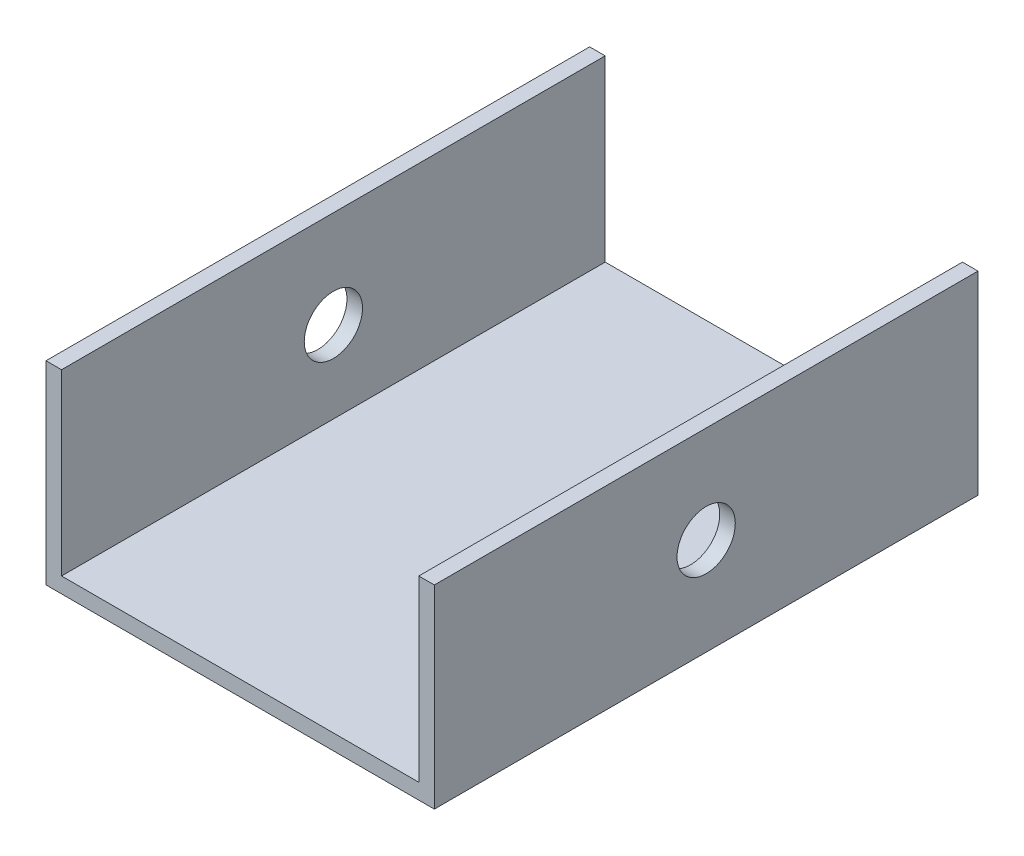
SolidWorks part; units mm, degrees
ref_plane "Front Plane" through (0, 0, 0) normal (0, 0, 1) x (1, 0, 0)
ref_plane "Top Plane" through (0, 0, 0) normal (0, 1, 0) x (1, 0, 0)
ref_plane "Right Plane" through (0, 0, 0) normal (1, 0, 0) x (0, 0, -1)
sketch "Sketch1" plane through (0, 0, 0) normal (0, 0, 1) x (1, 0, 0)
  line L0 (-38.8242, 25.8663) -> (-34.8242, 25.8663)
  line L1 (57.1758, 25.8663) -> (61.1758, 25.8663)
  line L2 (-38.8242, 25.8663) -> (-38.8242, -24.1337)
  line L3 (-38.8242, -24.1337) -> (61.1758, -24.1337)
  line L4 (61.1758, 25.8663) -> (61.1758, -24.1337)
  line L5 (-34.8242, 25.8663) -> (-34.8242, -20.1337)
  line L6 (-34.8242, -20.1337) -> (57.1758, -20.1337)
  line L7 (57.1758, 25.8663) -> (57.1758, -20.1337)
  dimension "D1" = 50
  dimension "D2" = 100
  dimension "D3" = 92
  dimension "D4" = 46
  dimension "D5" = 4
  dimension "D6" = 4
extrude "Boss-Extrude1" add sketch "Sketch1" along normal blind 140
sketch "Sketch2" plane through (61.1758, 0, 0) normal (1, 0, 0) x (0, 0, -1)
  line L0 (-140, 25.8663) -> (0, 25.8663) construction
  line L1 (0, -24.1337) -> (0, 25.8663) construction
  circle A0 centre (-70, 0.8663) radius 7.5
  dimension "D1" = 15
  dimension "D2" = 25
  dimension "D3" = 70
extrude "Cut-Extrude1" cut sketch "Sketch2" against normal through all both and the other way through all
